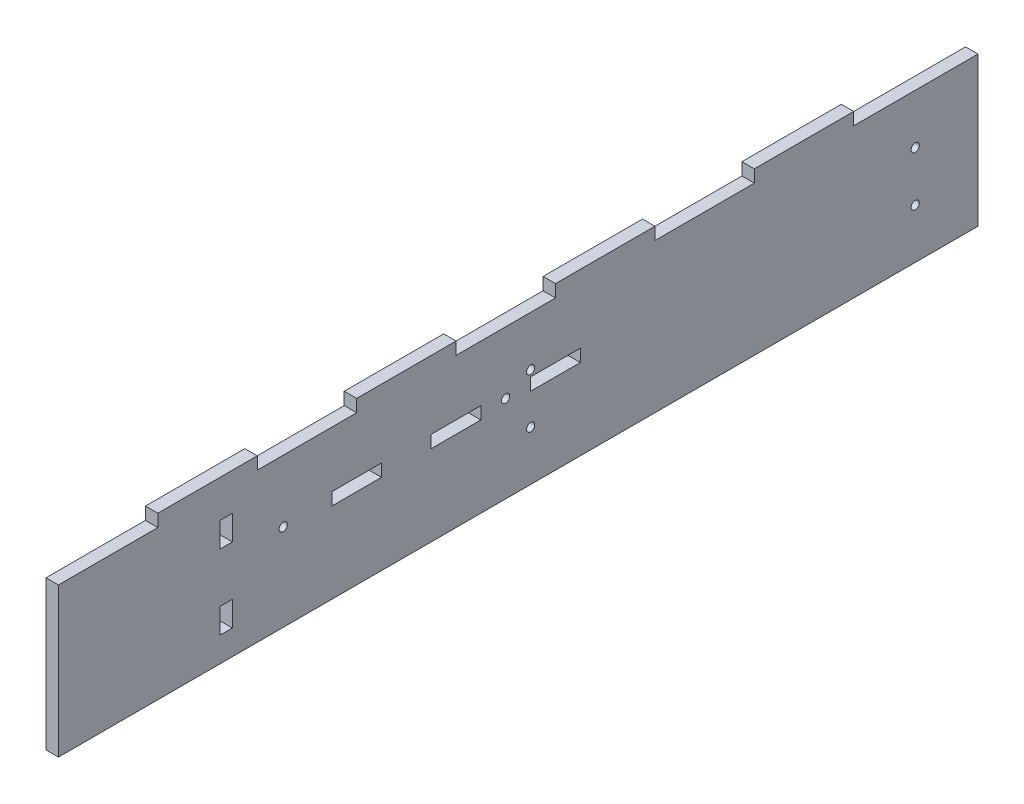
SolidWorks part; units mm, degrees
material "Pine"
ref_plane "Front Plane" through (0, 0, 0) normal (0, 0, 1) x (1, 0, 0)
ref_plane "Top Plane" through (0, 0, 0) normal (0, 1, 0) x (1, 0, 0)
ref_plane "Right Plane" through (0, 0, 0) normal (1, 0, 0) x (0, 0, -1)
sketch "Sketch1" plane through (0, 0, 0) normal (0, 0, 1) x (1, 0, 0)
  line L1 (-38.1, -38.1) -> (-44.45, -38.1)
  line L2 (-38.1, -38.1) -> (-38.1, 38.1)
  line L3 (-38.1, 38.1) -> (-44.45, 38.1)
  line L4 (-44.45, -38.1) -> (-44.45, 38.1)
extrude "Boss-Extrude1" add sketch "Sketch1" against normal up to surface (457.2 mm away)
sketch "Sketch2" plane through (0, 38.1, 0) normal (0, 1, 0) x (1, 0, 0)
  line L0 (-44.45, 457.2) -> (-44.45, 0) construction
  line L1 (-44.45, 406.4) -> (-38.1, 406.4)
  line L2 (-44.45, 406.4) -> (-44.45, 355.6)
  line L3 (-44.45, 355.6) -> (-38.1, 355.6)
  line L4 (-38.1, 406.4) -> (-38.1, 355.6)
  line L5 (-38.1, 406.4) -> (-44.45, 406.4) construction
  line L6 (-38.1, 457.2) -> (-38.1, 0) construction
  line L7 (-44.45, 355.6) -> (-38.1, 355.6) construction
  line L8 (-38.1, 203.2) -> (-44.45, 203.2) construction
  line L9 (-44.45, 304.8) -> (-38.1, 304.8)
  line L10 (-44.45, 304.8) -> (-44.45, 254)
  line L11 (-44.45, 254) -> (-38.1, 254)
  line L12 (-38.1, 304.8) -> (-38.1, 254)
  line L13 (-44.45, 203.2) -> (-38.1, 203.2)
  line L14 (-44.45, 203.2) -> (-44.45, 152.4)
  line L15 (-44.45, 152.4) -> (-38.1, 152.4)
  line L16 (-38.1, 203.2) -> (-38.1, 152.4)
  line L17 (-44.45, 152.4) -> (-38.1, 152.4) construction
  line L18 (-44.45, 50.8) -> (-38.1, 50.8) construction
  line L19 (-44.45, 101.6) -> (-38.1, 101.6)
  line L20 (-44.45, 101.6) -> (-44.45, 50.8)
  line L21 (-44.45, 50.8) -> (-38.1, 50.8)
  line L22 (-38.1, 101.6) -> (-38.1, 50.8)
  line L23 (-38.1, 101.6) -> (-44.45, 101.6) construction
  line L24 (-44.45, 254) -> (-38.1, 254) construction
  line L25 (-38.1, 304.8) -> (-44.45, 304.8) construction
extrude "Boss-Extrude2" add sketch "Sketch2" along normal up to surface (6.35 mm away)
sketch "Sketch3" plane through (-38.1, 0, 0) normal (1, 0, 0) x (0, 0, -1)
  line L1 (88.9, 25.4) -> (82.55, 25.4)
  line L2 (88.9, 25.4) -> (88.9, 12.7)
  line L3 (88.9, 12.7) -> (82.55, 12.7)
  line L4 (82.55, 25.4) -> (82.55, 12.7)
  line L5 (88.9, -12.7) -> (82.55, -12.7)
  line L6 (88.9, -12.7) -> (88.9, -25.4)
  line L7 (88.9, -25.4) -> (82.55, -25.4)
  line L8 (82.55, -12.7) -> (82.55, -25.4)
extrude "Cut-Extrude1" cut sketch "Sketch3" against normal through all
sketch "Sketch7" plane through (-44.45, 0, 0) normal (-1, 0, 0) x (0, 0, 1)
  circle A0 centre (-241.3, -12.7) radius 2.0955
  circle A1 centre (-241.3, 12.7) radius 2.0955
  circle A2 centre (-437.8325, -12.7) radius 2.0955
  circle A3 centre (-437.8325, 12.7) radius 2.0955
  circle A4 centre (-241.3, 12.7) radius 2.0955 construction
  circle A5 centre (-241.3, -12.7) radius 2.0955 construction
  circle A6 centre (-437.8325, 12.7) radius 2.0955 construction
  circle A7 centre (-437.8325, -12.7) radius 2.0955 construction
extrude "Cut-Extrude2" cut sketch "Sketch7" against normal through all
sketch "Sketch9" plane through (-44.45, 0, 0) normal (-1, 0, 0) x (0, 0, 1)
  line L0 (-230.6506, 9.525) -> (-226.3834, 3.175) construction
  line L1 (-266.7, 3.175) -> (-241.3, 3.175)
  line L2 (-266.7, 3.175) -> (-266.7, 9.525)
  line L3 (-266.7, 9.525) -> (-241.3, 9.525)
  line L4 (-241.3, 3.175) -> (-241.3, 9.525)
  line L5 (-215.9, 3.175) -> (-190.5, 3.175)
  line L6 (-215.9, 3.175) -> (-215.9, 9.525)
  line L7 (-215.9, 9.525) -> (-190.5, 9.525)
  line L8 (-190.5, 3.175) -> (-190.5, 9.525)
  line L9 (-165.1, 3.175) -> (-139.7, 3.175)
  line L10 (-165.1, 3.175) -> (-165.1, 9.525)
  line L11 (-165.1, 9.525) -> (-139.7, 9.525)
  line L12 (-139.7, 3.175) -> (-139.7, 9.525)
  line L13 (-230.6506, 3.175) -> (-226.3834, 9.525) construction
  line L14 (-117.0138, 9.525) -> (-112.7466, 3.175) construction
  line L15 (-117.0138, 3.175) -> (-112.7466, 9.525) construction
  circle A0 centre (-114.8802, 6.35) radius 2.0955
  circle A1 centre (-228.517, 6.35) radius 2.0955
  dimension "D1" = 4.191
  dimension "D2" = 4.191
extrude "Cut-Extrude3" cut sketch "Sketch9" against normal blind 6.35
sketch "Sketch11" plane through (0, 0, -457.2) normal (0, 0, -1) x (-1, 0, 0)
  line L1 (44.45, -38.1) -> (38.1, -38.1)
  line L2 (44.45, -38.1) -> (44.45, 38.1)
  line L3 (44.45, 38.1) -> (38.1, 38.1)
  line L4 (38.1, -38.1) -> (38.1, 38.1)
extrude "Boss-Extrude5" add sketch "Sketch11" along normal blind 12.7
